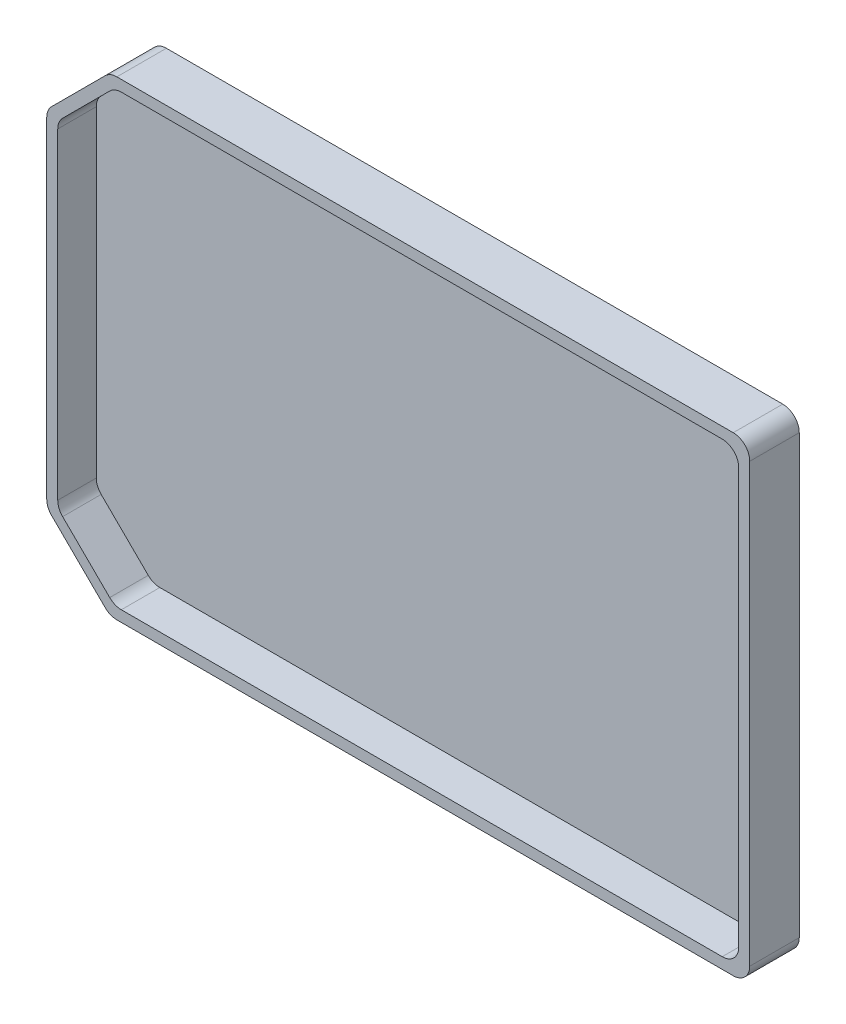
SolidWorks part; units mm, degrees
material "Acrylic (Medium-high impact)"
ref_plane "Front Plane" through (0, 0, 0) normal (0, 0, 1) x (1, 0, 0)
ref_plane "Top Plane" through (0, 0, 0) normal (0, 1, 0) x (1, 0, 0)
ref_plane "Right Plane" through (0, 0, 0) normal (1, 0, 0) x (0, 0, -1)
sketch "Plate Lid" plane through (0, 0, 0) normal (0, 0, 1) x (1, 0, 0)
  line L0 (-63.4623, 42.076) -> (64.2977, 42.076)
  line L1 (-63.4623, 42.076) -> (-63.4623, -43.394)
  line L2 (-63.4623, -43.394) -> (64.2977, -43.394)
  line L3 (64.2977, 42.076) -> (64.2977, -43.394)
  line L4 (-63.4623, 42.076) -> (64.2977, -43.394) construction
  line L5 (-63.4623, -43.394) -> (64.2977, 42.076) construction
  point P0 (0.4177, -0.659)
  dimension "D1" = 127.76
  dimension "D2" = 85.47
extrude "Plate Lid (9mm)" add sketch "Plate Lid" along normal blind 9
sketch "Sketch2" plane through (0, 0, 0) normal (0, 0, 1) x (1, 0, 0)
  line L0 (-63.4623, -43.394) -> (-51.9623, -43.394)
  line L3 (-63.4623, 42.076) -> (-63.4623, -43.394) construction
  line L5 (-53.9623, -41.524) -> (-61.4623, -41.524) construction
  line L6 (-61.4623, 40.076) -> (-61.4623, 32.576) construction
  line L7 (-61.4623, 32.576) -> (-53.9623, 40.076) construction
  line L8 (-53.9623, 40.076) -> (-61.4623, 40.076) construction
  line L9 (-61.4623, -41.524) -> (-61.4623, -34.024) construction
  line L10 (-61.4623, -34.024) -> (-53.9623, -41.524) construction
  line L12 (-63.4623, -43.394) -> (64.2977, -43.394) construction
  line L13 (-51.9623, -43.394) -> (-63.4623, -32.024)
  line L14 (-63.4623, -32.024) -> (-63.4623, -43.394)
  line L15 (-63.4623, 30.576) -> (-51.9623, 42.076)
  line L17 (64.2977, 42.076) -> (-63.4623, 42.076) construction
  line L18 (-51.9623, 42.076) -> (-63.4623, 42.076)
  line L19 (-63.4623, 42.076) -> (-63.4623, 30.576)
  dimension "D1" = 2
  dimension "D2" = 2
  dimension "D3" = 2
  dimension "D4" = 7.5
  dimension "D5" = 7.5
  dimension "D6" = 7.5
  dimension "D7" = 7.5
extrude "Style" cut sketch "Sketch2" along normal through all
shell "Lid Thickness" thickness 2
fillet "Fillet2" radius 3 12 edges at (62.2977, 40.076, 5.5) (62.2977, -41.394, 5.5) (64.2977, -43.394, 4.5) (64.2977, 42.076, 4.5) (-63.4623, 30.576, 4.5) (-51.9623, 42.076, 4.5) (-51.1339, 40.076, 5.5) (-61.4623, 29.7475, 5.5) (-51.1405, -41.394, 5.5) (-51.9623, -43.394, 4.5) (-61.4623, -31.1889, 5.5) (-63.4623, -32.024, 4.5)
